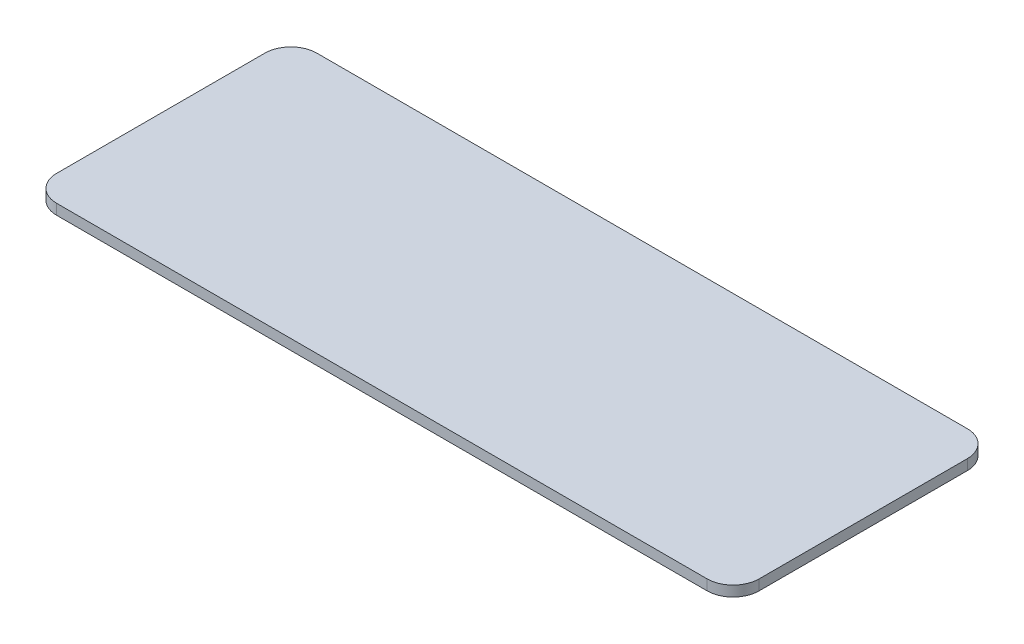
SolidWorks part; units mm, degrees
ref_plane "Ebene vorne" through (0, 0, 0) normal (0, 0, 1) x (1, 0, 0)
ref_plane "Ebene oben" through (0, 0, 0) normal (0, 1, 0) x (1, 0, 0)
ref_plane "Ebene rechts" through (0, 0, 0) normal (1, 0, 0) x (0, 0, -1)
sketch "Skizze1" plane through (0, 0, 0) normal (0, 1, 0) x (1, 0, 0)
  line L1 (-50, 20) -> (50, 20)
  line L2 (-54, 16) -> (-54, -16)
  line L3 (-50, -20) -> (50, -20)
  line L4 (54, 16) -> (54, -16)
  line L5 (-54, 20) -> (54, -20) construction
  line L6 (-54, -20) -> (54, 20) construction
  arc A0 (50, 20) -> (54, 16) centre (50, 16) cw
  arc A1 (50, -20) -> (54, -16) centre (50, -16) ccw
  arc A2 (-54, -16) -> (-50, -20) centre (-50, -16) ccw
  arc A3 (-50, 20) -> (-54, 16) centre (-50, 16) ccw
  point P0 (0, 0)
  dimension "D3" = 4
  dimension "D1" = 40
  dimension "D2" = 108
extrude "Aufsatz-Linear austragen1" add sketch "Skizze1" along normal blind 1.6
